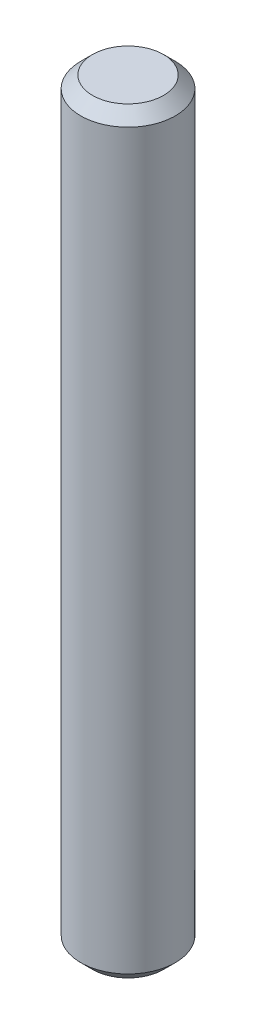
SolidWorks part; units mm, degrees
material "Plain Carbon Steel"
ref_plane "Front Plane" through (0, 0, 0) normal (1, 0, 0) x (0, 1, 0)
ref_plane "Top Plane" through (0, 0, 0) normal (0, 0, 1) x (0, 1, 0)
ref_plane "Right Plane" through (0, 0, 0) normal (0, 1, 0) x (-1, 0, 0)
sketch "Sketch1" plane through (0, 0, 0) normal (1, 0, 0) x (0, 1, 0)
  line L0 (-12.7, 0) -> (12.7, 0)
  line L1 (-12.7, 0) -> (-12.7, 1.1913)
  line L2 (-12.7, 1.1913) -> (-12.3038, 1.5875)
  line L3 (-12.3038, 1.5875) -> (12.3038, 1.5875)
  line L4 (12.3038, 1.5875) -> (12.7, 1.1913)
  line L5 (12.7, 1.1913) -> (12.7, 0)
  point P4 (0, 0)
  dimension "D1" = 25.4
  dimension "D2" = 1.5875
  dimension "D3" = 45
  dimension "D4" = 0.3962
revolve "Revolve1" add sketch "Sketch1" angle 360 about L0
